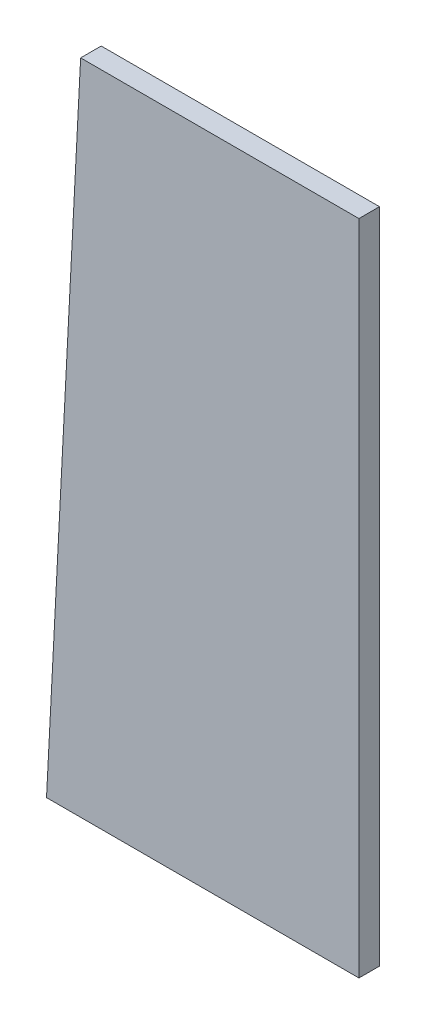
SolidWorks part; units mm, degrees
material "AISI 4340 Steel, normalized"
ref_plane "Front Plane" through (0, 0, 0) normal (0, 0, 1) x (1, 0, 0)
ref_plane "Top Plane" through (0, 0, 0) normal (0, 1, 0) x (1, 0, 0)
ref_plane "Right Plane" through (0, 0, 0) normal (1, 0, 0) x (0, 0, -1)
sketch "Sketch1" plane through (0, 0, 0) normal (0, 0, 1) x (1, 0, 0)
  line L0 (-12.065, -25.4) -> (-9.4291, 25.4)
  line L1 (-12.065, 25.4) -> (12.065, 25.4)
  line L2 (-12.065, 25.4) -> (-12.065, -25.4)
  line L3 (-12.065, -25.4) -> (12.065, -25.4)
  line L4 (12.065, 25.4) -> (12.065, -25.4)
  line L5 (-12.065, 25.4) -> (12.065, -25.4) construction
  line L6 (-12.065, -25.4) -> (12.065, 25.4) construction
  point P0 (0, 0)
  dimension "D1" = 50.8
  dimension "D2" = 24.13
  dimension "D3" = 2.97
extrude "Boss-Extrude1" add sketch "Sketch1" along normal blind 1.5875
